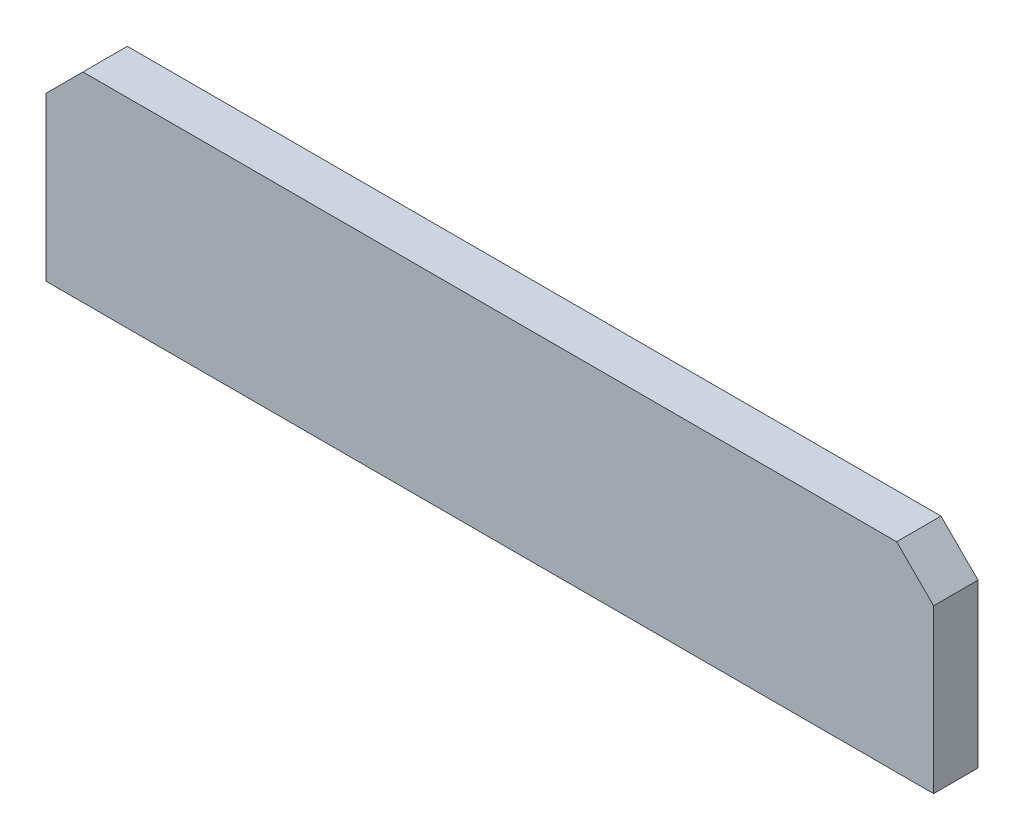
SolidWorks part; units mm, degrees
material "Q355"
ref_plane "前视基准面" through (0, 0, 0) normal (0, 0, 1) x (1, 0, 0)
ref_plane "上视基准面" through (0, 0, 0) normal (0, 1, 0) x (1, 0, 0)
ref_plane "右视基准面" through (0, 0, 0) normal (1, 0, 0) x (0, 0, -1)
sketch "草图1" plane through (0, 0, 0) normal (0, 0, 1) x (1, 0, 0)
  line L1 (-60, -13.5) -> (60, -13.5)
  line L2 (-60, -13.5) -> (-60, 13.5)
  line L3 (-60, 13.5) -> (60, 13.5)
  line L4 (60, -13.5) -> (60, 13.5)
  line L5 (-60, -13.5) -> (60, 13.5) construction
  line L6 (-60, 13.5) -> (60, -13.5) construction
  point P0 (0, 0)
  dimension "D1" = 120
  dimension "D2" = 27
extrude "凸台-拉伸1" add sketch "草图1" along normal blind 6
chamfer "倒角1" distance 5 angle 45 2 edges at (-60, 13.5, 3) (60, 13.5, 3)
